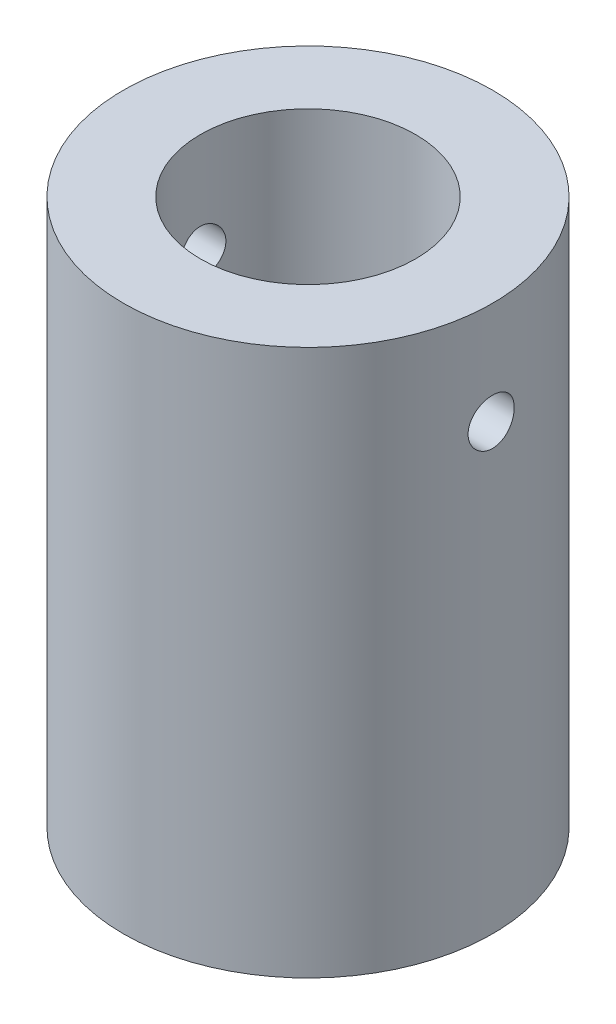
SolidWorks part; units mm, degrees
ref_plane "Спереди" through (0, 0, 0) normal (0, 0, 1) x (1, 0, 0)
ref_plane "Сверху" through (0, 0, 0) normal (0, 1, 0) x (1, 0, 0)
ref_plane "Справа" through (0, 0, 0) normal (1, 0, 0) x (0, 0, -1)
sketch "Эскиз1" plane through (0, 0, 0) normal (0, 1, 0) x (1, 0, 0)
  circle A0 centre (0, 0) radius 8
  circle A1 centre (0, 0) radius 12
extrude "Вытянуть1" add sketch "Эскиз1" along normal blind 7.5
sketch "Эскиз2" plane through (0, 7.5, 0) normal (0, 1, 0) x (1, 0, 0)
  circle A0 centre (0, 0) radius 12
extrude "Вытянуть2" add sketch "Эскиз2" along normal blind 28
sketch "Эскиз3" plane through (0, 7.5, 0) normal (0, -1, 0) x (1, 0, 0)
  line L1 (4.6754, 1.6251) -> (-1.6251, 4.6754)
  line L2 (-1.6251, 4.6754) -> (-4.6754, -1.6251)
  line L3 (-4.6754, -1.6251) -> (1.6251, -4.6754)
  line L4 (1.6251, -4.6754) -> (4.6754, 1.6251)
  circle A0 centre (0, 0) radius 3.5 construction
  dimension "D1" = 7
extrude "Вытянуть3" cut sketch "Эскиз3" against normal blind 11
sketch "Эскиз4" plane through (0, 35.5, 0) normal (0, 1, 0) x (1, 0, 0)
  circle A0 centre (0, 0) radius 7
extrude "Вытянуть4" cut sketch "Эскиз4" against normal blind 16
sketch "Эскиз5" plane through (0, 0, 0) normal (1, 0, 0) x (0, 0, -1)
  circle A0 centre (0, 28.8314) radius 1.5
extrude "Вытянуть5" cut sketch "Эскиз5" against normal mid plane 60
